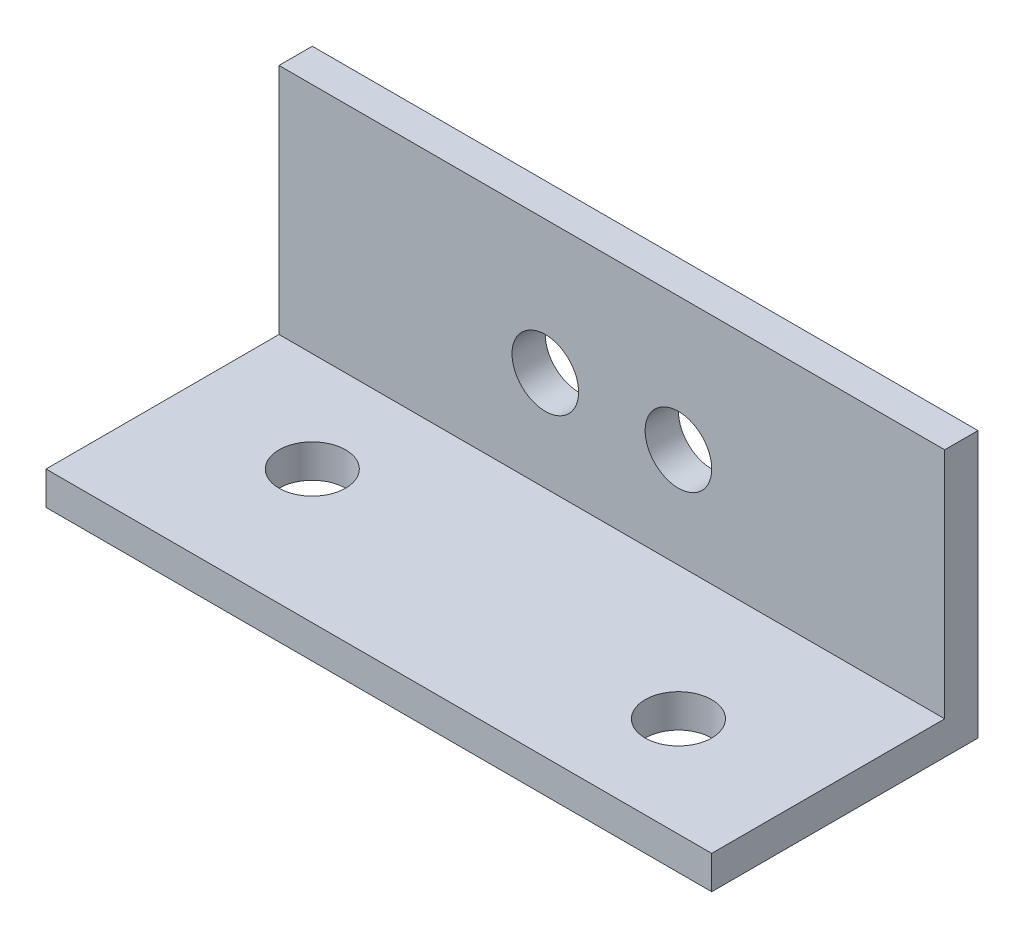
SolidWorks part; units mm, degrees
material "6061-T6 (SS)"
ref_plane "Front Plane" through (0, 0, 0) normal (0, 0, 1) x (1, 0, 0)
ref_plane "Top Plane" through (0, 0, 0) normal (0, 1, 0) x (1, 0, 0)
ref_plane "Right Plane" through (0, 0, 0) normal (1, 0, 0) x (0, 0, -1)
sketch "Sketch1" plane through (0, 0, 0) normal (0, 1, 0) x (1, 0, 0)
  line L1 (-31.75, -12.7) -> (31.75, -12.7)
  line L2 (-31.75, -12.7) -> (-31.75, 12.7)
  line L3 (-31.75, 12.7) -> (31.75, 12.7)
  line L4 (31.75, -12.7) -> (31.75, 12.7)
  line L5 (-31.75, -12.7) -> (31.75, 12.7) construction
  line L6 (-31.75, 12.7) -> (31.75, -12.7) construction
  point P0 (0, 0)
  dimension "D1" = 25.4
  dimension "D2" = 63.5
extrude "Boss-Extrude1" add sketch "Sketch1" along normal blind 3.175
sketch "Sketch2" plane through (0, 3.175, 0) normal (0, 1, 0) x (1, 0, 0)
  line L0 (31.75, -12.7) -> (31.75, 12.7) construction
  line L1 (-31.75, 12.7) -> (31.75, 12.7)
  line L2 (-31.75, 12.7) -> (-31.75, 9.525)
  line L3 (-31.75, 9.525) -> (31.75, 9.525)
  line L4 (31.75, 12.7) -> (31.75, 9.525)
  dimension "D1" = 3.175
extrude "Boss-Extrude2" add sketch "Sketch2" along normal blind 22.225
sketch "Sketch3" plane through (0, 0, -9.525) normal (0, 0, 1) x (1, 0, 0)
  line L0 (-31.75, 25.4) -> (31.75, 25.4) construction
  line L1 (-31.75, 25.4) -> (-31.75, 3.175) construction
  line L2 (31.75, 25.4) -> (31.75, 3.175) construction
  circle A0 centre (-6.35, 12.7) radius 3.175
  circle A1 centre (6.35, 12.7) radius 3.175
  dimension "D1" = 6.35
  dimension "D2" = 12.7
  dimension "D3" = 25.4
  dimension "D4" = 6.35
  dimension "D5" = 25.4
  dimension "D6" = 12.7
extrude "Cut-Extrude1" cut sketch "Sketch3" against normal blind 3.175
sketch "Sketch4" plane through (0, 3.175, 0) normal (0, 1, 0) x (1, 0, 0)
  line L0 (-31.75, -12.7) -> (31.75, -12.7) construction
  line L1 (-31.75, 9.525) -> (-31.75, -12.7) construction
  line L2 (31.75, -12.7) -> (31.75, 9.525) construction
  line L3 (31.75, 12.7) -> (-31.75, 12.7) construction
  circle A0 centre (-19.05, 0) radius 3.175
  circle A1 centre (19.05, -3.175) radius 3.175
  dimension "D1" = 6.35
  dimension "D2" = 12.7
  dimension "D3" = 12.7
  dimension "D4" = 6.35
  dimension "D5" = 15.875
  dimension "D6" = 12.7
extrude "Cut-Extrude2" cut sketch "Sketch4" against normal blind 3.175
